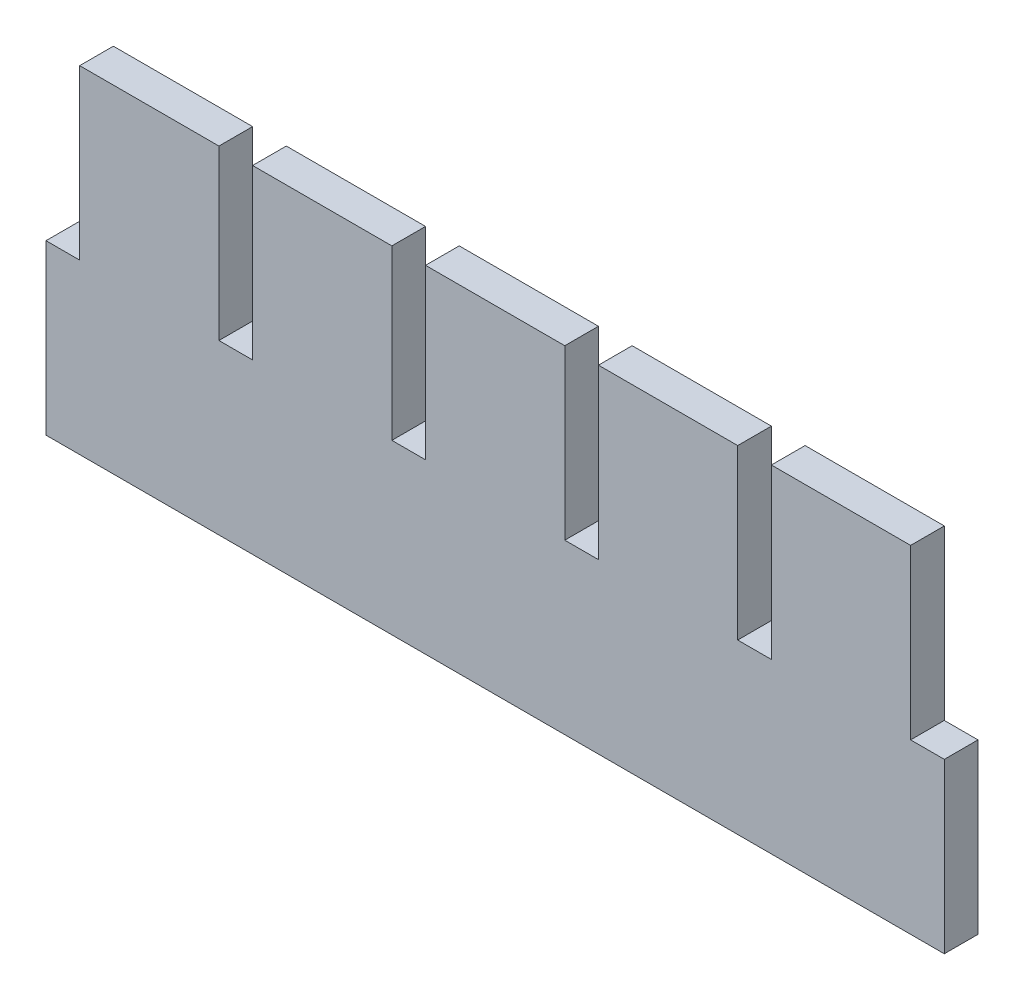
SolidWorks part; units mm, degrees
ref_plane "Front Plane" through (0, 0, 0) normal (0, 0, 1) x (1, 0, 0)
ref_plane "Top Plane" through (0, 0, 0) normal (0, 1, 0) x (1, 0, 0)
ref_plane "Right Plane" through (0, 0, 0) normal (1, 0, 0) x (0, 0, -1)
sketch "Sketch1" plane through (0, 0, 0) normal (0, 0, 1) x (1, 0, 0)
  line L0 (3, 15) -> (15.4, 15) construction
  line L1 (0, 0) -> (80, 0)
  line L2 (0, 0) -> (0, 15)
  line L3 (3, 30) -> (15.4, 30)
  line L4 (80, 0) -> (80, 15)
  line L5 (64.6, 30) -> (77, 30)
  line L6 (49.2, 30) -> (61.6, 30)
  line L7 (0, 15) -> (3, 15)
  line L8 (3, 30) -> (3, 15)
  line L9 (33.8, 30) -> (46.2, 30)
  line L10 (18.4, 30) -> (30.8, 30)
  line L11 (80, 15) -> (77, 15)
  line L12 (77, 30) -> (77, 15)
  line L14 (15.4, 30) -> (15.4, 15)
  line L15 (15.4, 15) -> (18.4, 15)
  line L16 (18.4, 30) -> (18.4, 15)
  line L18 (30.8, 30) -> (30.8, 15)
  line L19 (30.8, 15) -> (33.8, 15)
  line L20 (33.8, 30) -> (33.8, 15)
  line L22 (46.2, 30) -> (46.2, 15)
  line L23 (46.2, 15) -> (49.2, 15)
  line L24 (49.2, 30) -> (49.2, 15)
  line L26 (61.6, 30) -> (61.6, 15)
  line L27 (61.6, 15) -> (64.6, 15)
  line L28 (64.6, 30) -> (64.6, 15)
  line L29 (18.4, 15) -> (30.8, 15) construction
  line L30 (33.8, 15) -> (46.2, 15) construction
  line L31 (49.2, 15) -> (61.6, 15) construction
  line L32 (64.6, 15) -> (77, 15) construction
  dimension "D1" = 30
  dimension "D2" = 15
  dimension "D3" = 3
extrude "Boss-Extrude1" add sketch "Sketch1" along normal blind 3
